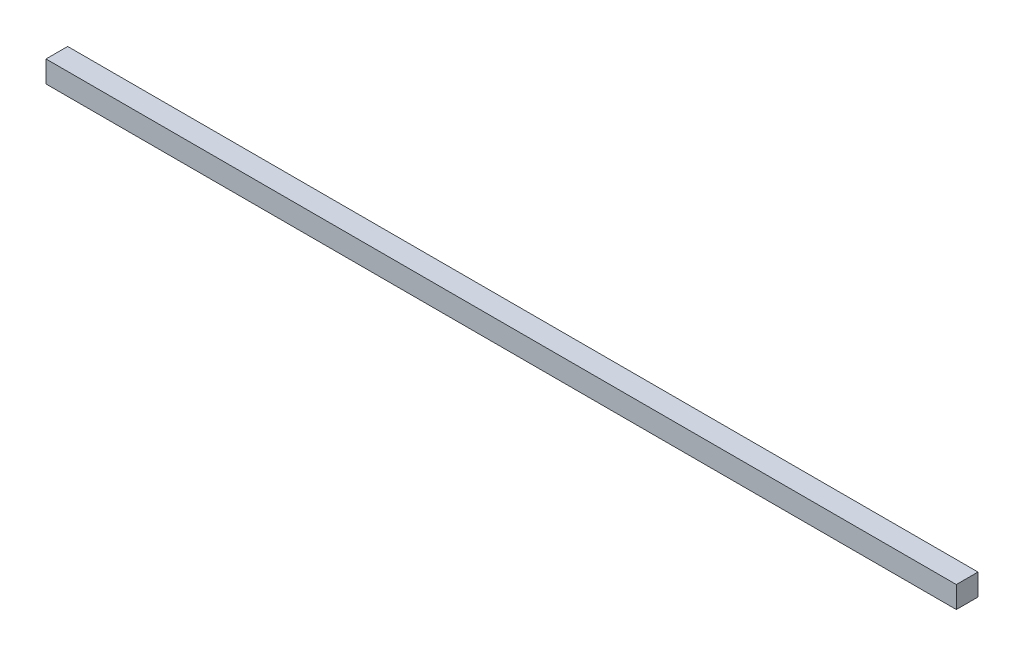
SolidWorks part; units mm, degrees
ref_plane "Front Plane" through (0, 0, 0) normal (0, 0, 1) x (1, 0, 0)
ref_plane "Top Plane" through (0, 0, 0) normal (0, 1, 0) x (1, 0, 0)
ref_plane "Right Plane" through (0, 0, 0) normal (1, 0, 0) x (0, 0, -1)
sketch "Sketch1" plane through (0, 0, 0) normal (0, 1, 0) x (1, 0, 0)
  line L1 (0, 0) -> (266.7, 0)
  line L2 (0, 0) -> (0, 6.35)
  line L3 (0, 6.35) -> (266.7, 6.35)
  line L4 (266.7, 0) -> (266.7, 6.35)
  dimension "D1" = 266.7
  dimension "D2" = 6.35
extrude "Boss-Extrude1" add sketch "Sketch1" along normal blind 6.35
